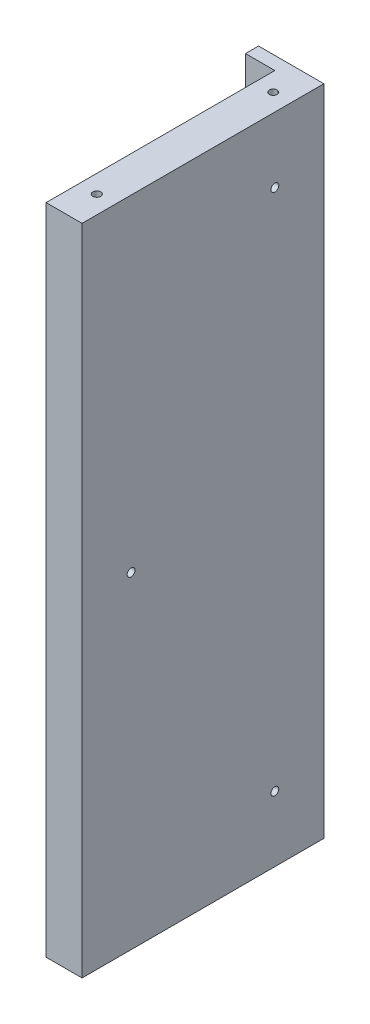
SolidWorks part; units mm, degrees
ref_plane "Front Plane" through (0, 0, 0) normal (0, 0, 1) x (1, 0, 0)
ref_plane "Top Plane" through (0, 0, 0) normal (0, 1, 0) x (1, 0, 0)
ref_plane "Right Plane" through (0, 0, 0) normal (1, 0, 0) x (0, 0, -1)
sketch "Sketch1" plane through (0, 0, 0) normal (0, 1, 0) x (1, 0, 0)
  line L1 (-10, 50) -> (10, 50)
  line L2 (-10, 50) -> (-10, -50)
  line L3 (-10, -50) -> (10, -50)
  line L4 (10, 50) -> (10, -50)
  line L5 (-10, 50) -> (10, -50) construction
  line L6 (-10, -50) -> (10, 50) construction
  point P0 (0, 0)
  dimension "D1" = 100
  dimension "D2" = 20
extrude "Boss-Extrude1" add sketch "Sketch1" along normal blind 200
sketch "Sketch2" plane through (0, 200, 0) normal (0, 1, 0) x (1, 0, 0)
  line L1 (-10, -50) -> (-1, -50)
  line L2 (-10, -50) -> (-10, 20)
  line L3 (-10, 20) -> (-1, 20)
  line L4 (-1, -50) -> (-1, 20)
  dimension "D1" = 9
  dimension "D2" = 70
extrude "Cut-Extrude1" cut sketch "Sketch2" against normal through all
hole_wizard "M2 Clearance Hole1" positions "Sketch6" profile "Sketch5" hole size "M2" standard "ANSI Metric"
sketch "Sketch6" plane through (0, 200, 0) normal (0, 1, 0) x (1, 0, 0)
  line L0 (10, -50) -> (10, 50) construction
  line L1 (10, 50) -> (-10, 50) construction
  point P0 (4.5, 40)
  point P2 (4.5, -40)
  dimension "D1" = 5.5
  dimension "D2" = 5.5
  dimension "D3" = 10
  dimension "D4" = 80
sketch "Sketch5" plane through (4.5, 200, -40) normal (1, 0, 0) x (0, 0, 1)
  line L0 (0, 0) -> (0, 4.721)
  line L1 (0, 4.721) -> (1.2, 4)
  line L2 (1.2, 4) -> (1.2, 0)
  line L5 (1.2, 0) -> (0, 0)
  line L10 (0, 4.721) -> (-1.2, 4) construction
  line L11 (0, -6.35) -> (0, 107.95) construction
  dimension "Hole Dia." = 2.4
  dimension "Hole Depth" = 4
  dimension "Drill Angle" = 118
hole_wizard "M2 Clearance Hole2" positions "Sketch8" profile "Sketch7" hole size "M2" standard "ANSI Metric"
sketch "Sketch8" plane through (0, 0, 0) normal (0, -1, 0) x (-1, 0, 0)
  line L0 (-10, -50) -> (-10, 50) construction
  line L1 (-10, 50) -> (10, 50) construction
  point P0 (-4.5, 40)
  point P2 (-4.5, -40)
  dimension "D1" = 5.5
  dimension "D2" = 5.5
  dimension "D3" = 10
  dimension "D4" = 80
sketch "Sketch7" plane through (4.5, 0, -40) normal (1, 0, 0) x (0, 0, -1)
  line L0 (0, 0) -> (0, 4.721)
  line L1 (0, 4.721) -> (1.2, 4)
  line L2 (1.2, 4) -> (1.2, 0)
  line L5 (1.2, 0) -> (0, 0)
  line L10 (0, 4.721) -> (-1.2, 4) construction
  line L11 (0, -6.35) -> (0, 107.95) construction
  dimension "Hole Dia." = 2.4
  dimension "Hole Depth" = 4
  dimension "Drill Angle" = 118
hole_wizard "M2 Clearance Hole4" positions "Sketch12" profile "Sketch11" hole size "M2" standard "ANSI Metric" end condition through all
sketch "Sketch12" plane through (0, 0, -50) normal (0, 0, -1) x (-1, 0, 0)
  line L0 (-10, 200) -> (10, 200) construction
  line L1 (-10, 0) -> (10, 0) construction
  line L2 (10, 200) -> (10, 0) construction
  point P0 (5, 190)
  point P2 (5, 10)
  dimension "D1" = 10
  dimension "D2" = 10
  dimension "D3" = 5
  dimension "D4" = 5
sketch "Sketch11" plane through (-5, 190, -50) normal (1, 0, 0) x (0, 1, 0)
  line L0 (0, 0) -> (0, 100)
  line L1 (0, 100) -> (1.2, 100)
  line L2 (1.2, 100) -> (1.2, 0)
  line L5 (1.2, 0) -> (0, 0)
  line L11 (0, -6.35) -> (0, 107.95) construction
  dimension "Thru Hole Dia." = 2.4
  dimension "Thru Hole Depth" = 100
sketch "Sketch13" plane through (0, 0, 0) normal (0, -1, 0) x (1, 0, 0)
  line L0 (-10, -50) -> (-10, -20) construction
  line L1 (10, -50) -> (-10, -50)
  line L2 (10, -50) -> (10, -24)
  line L3 (10, -24) -> (-10, -24)
  line L4 (-10, -50) -> (-10, -24)
  dimension "D1" = 26
extrude "Cut-Extrude2" cut sketch "Sketch13" against normal through all
hole_wizard "M2 Clearance Hole5" positions "Sketch15" profile "Sketch14" hole size "M2" standard "ANSI Metric"
sketch "Sketch15" plane through (0, 0, 0) normal (0, -1, 0) x (-1, 0, 0)
  line L0 (-10, -50) -> (-10, 24) construction
  line L1 (-10, 24) -> (10, 24) construction
  point P0 (-4.5, 14)
  dimension "D1" = 5.5
  dimension "D2" = 10
sketch "Sketch14" plane through (4.5, 0, -14) normal (1, 0, 0) x (0, 0, -1)
  line L0 (0, 0) -> (0, 11.721)
  line L1 (0, 11.721) -> (1.2, 11)
  line L2 (1.2, 11) -> (1.2, 0)
  line L5 (1.2, 0) -> (0, 0)
  line L10 (0, 11.721) -> (-1.2, 11) construction
  line L11 (0, -6.35) -> (0, 107.95) construction
  dimension "Hole Dia." = 2.4
  dimension "Hole Depth" = 11
  dimension "Drill Angle" = 118
hole_wizard "M2 Clearance Hole6" positions "Sketch17" profile "Sketch16" hole size "M2" standard "ANSI Metric"
sketch "Sketch17" plane through (0, 200, 0) normal (0, 1, 0) x (1, 0, 0)
  line L0 (10, -50) -> (10, 24) construction
  line L1 (10, 24) -> (-10, 24) construction
  point P0 (4.5, 14)
  dimension "D1" = 5.5
  dimension "D2" = 10
sketch "Sketch16" plane through (4.5, 200, -14) normal (1, 0, 0) x (0, 0, 1)
  line L0 (0, 0) -> (0, 11.721)
  line L1 (0, 11.721) -> (1.2, 11)
  line L2 (1.2, 11) -> (1.2, 0)
  line L5 (1.2, 0) -> (0, 0)
  line L10 (0, 11.721) -> (-1.2, 11) construction
  line L11 (0, -6.35) -> (0, 107.95) construction
  dimension "Hole Dia." = 2.4
  dimension "Hole Depth" = 11
  dimension "Drill Angle" = 118
hole_wizard "M2 Clearance Hole7" positions "Sketch19" profile "Sketch18" hole size "M2" standard "ANSI Metric"
sketch "Sketch19" plane through (10, 0, 0) normal (1, 0, 0) x (0, 0, -1)
  line L0 (-50, 0) -> (24, 0) construction
  line L1 (24, 200) -> (24, 0) construction
  line L2 (-50, 200) -> (24, 200) construction
  line L3 (-50, 200) -> (-50, 0) construction
  point P0 (9, 20)
  point P2 (9, 180)
  point P4 (-35, 100)
  dimension "D1" = 20
  dimension "D2" = 15
  dimension "D3" = 20
  dimension "D4" = 15
  dimension "D5" = 100
  dimension "D6" = 15
sketch "Sketch18" plane through (10, 20, -9) normal (0, 1, 0) x (0, 0, -1)
  line L0 (0, 0) -> (0, 11.721)
  line L1 (0, 11.721) -> (1.2, 11)
  line L2 (1.2, 11) -> (1.2, 0)
  line L5 (1.2, 0) -> (0, 0)
  line L10 (0, 11.721) -> (-1.2, 11) construction
  line L11 (0, -6.35) -> (0, 107.95) construction
  dimension "Hole Dia." = 2.4
  dimension "Hole Depth" = 11
  dimension "Drill Angle" = 118
